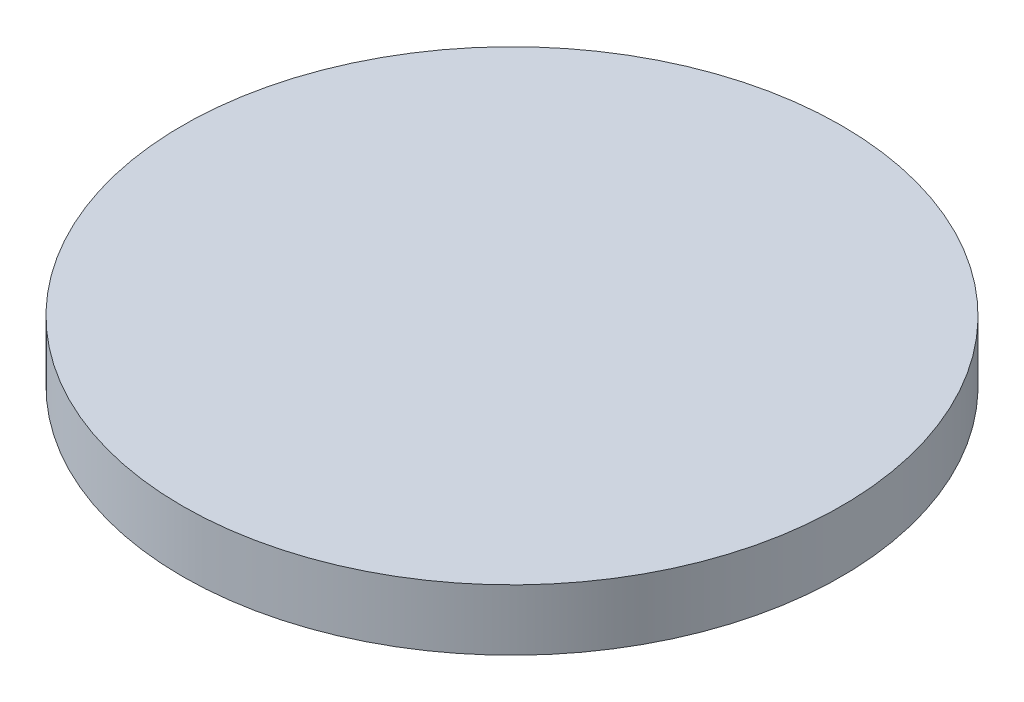
SolidWorks part; units mm, degrees
material "1060 Alloy"
ref_plane "Front Plane" through (0, 0, 0) normal (0, 0, 1) x (1, 0, 0)
ref_plane "Top Plane" through (0, 0, 0) normal (0, 1, 0) x (1, 0, 0)
ref_plane "Right Plane" through (0, 0, 0) normal (1, 0, 0) x (0, 0, -1)
sketch "Sketch1" plane through (0, 0, 0) normal (0, 1, 0) x (1, 0, 0)
  circle A0 centre (0, 0) radius 40
  dimension "D1" = 80
extrude "Boss-Extrude1" add sketch "Sketch1" along normal blind 7.4
